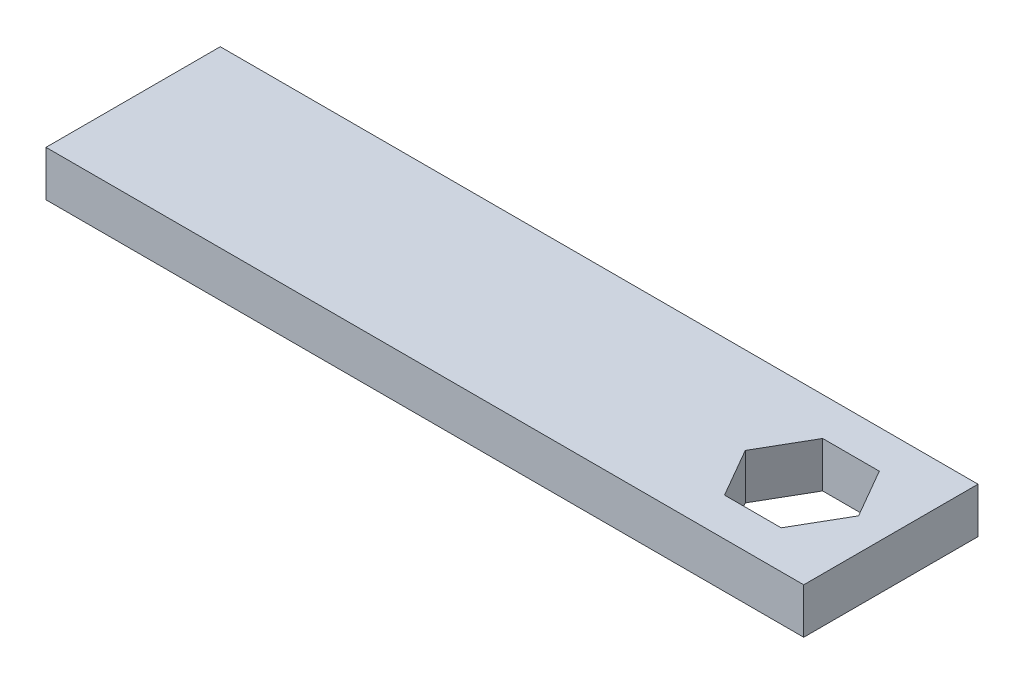
SolidWorks part; units mm, degrees
ref_plane "Płaszczyzna przednia" through (0, 0, 0) normal (0, 0, 1) x (1, 0, 0)
ref_plane "Płaszczyzna górna" through (0, 0, 0) normal (0, 1, 0) x (1, 0, 0)
ref_plane "Płaszczyzna prawa" through (0, 0, 0) normal (1, 0, 0) x (0, 0, -1)
sketch "Szkic2" plane through (0, 6, 0) normal (0, 1, 0) x (1, 0, 0)
  line L0 (84.158, -165.0778) -> (84.158, -188.0778)
  line L1 (84.158, -165.0778) -> (-15.842, -165.0778)
  line L2 (84.158, -188.0778) -> (-15.842, -188.0778)
  line L3 (-15.842, -165.0778) -> (-15.842, -188.0778)
  dimension "D1" = 23
  dimension "D2" = 100
extrude "Dodanie-wyciągnięcie1" add sketch "Szkic2" against normal blind 6
sketch "Szkic3" plane through (0, 6, 0) normal (0, 1, 0) x (1, 0, 0)
  line L0 (-15.842, -188.0778) -> (84.158, -188.0778) construction
  line L1 (64.943, -176.5778) -> (68.6813, -183.0528)
  line L2 (68.6813, -183.0528) -> (76.158, -183.0528)
  line L3 (76.158, -183.0528) -> (79.8963, -176.5778)
  line L4 (79.8963, -176.5778) -> (76.158, -170.1028)
  line L5 (76.158, -170.1028) -> (68.6813, -170.1028)
  line L6 (68.6813, -170.1028) -> (64.943, -176.5778)
  line L7 (84.158, -165.0778) -> (-15.842, -165.0778) construction
  line L8 (84.158, -188.0778) -> (84.158, -165.0778) construction
  circle A0 centre (72.4196, -176.5778) radius 6.475 construction
  dimension "D4" = 12.95
  dimension "D1" = 23
  dimension "D2" = 11.5
  dimension "D3" = 8
  dimension "D5" = 11.5
extrude "Wytnij-wyciągnięcie1" cut sketch "Szkic3" against normal blind 6
